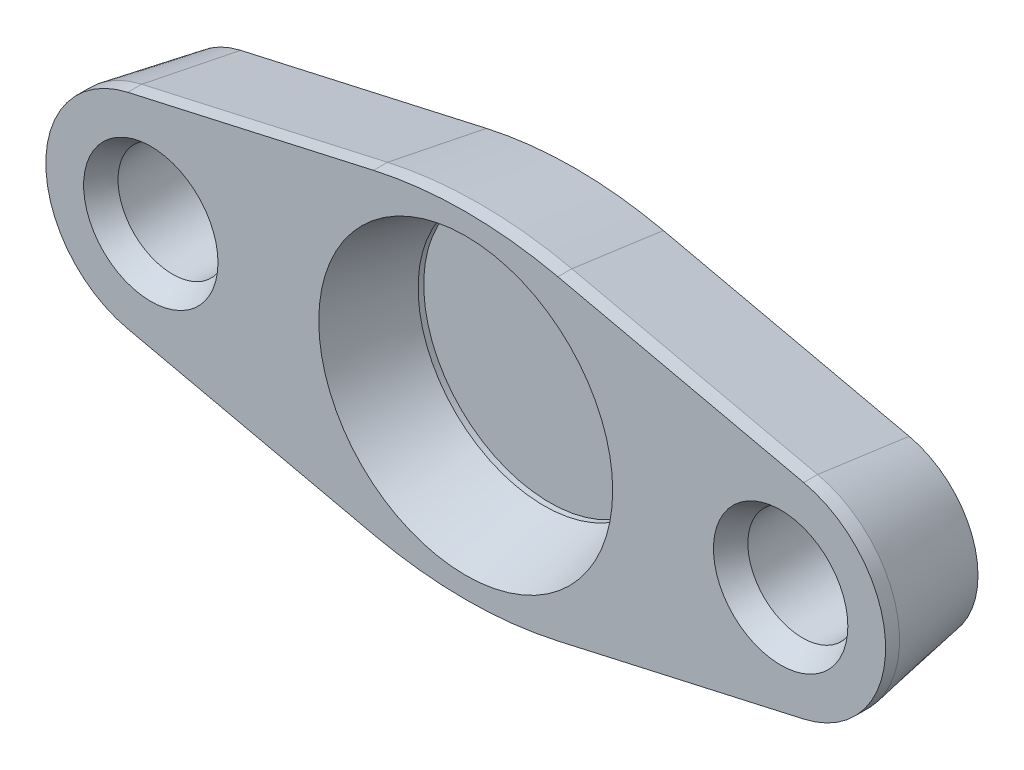
SolidWorks part; units mm, degrees
ref_plane "Front Plane" through (0, 0, 0) normal (0, 0, 1) x (1, 0, 0)
ref_plane "Top Plane" through (0, 0, 0) normal (0, 1, 0) x (1, 0, 0)
ref_plane "Right Plane" through (0, 0, 0) normal (1, 0, 0) x (0, 0, -1)
sketch "Sketch1" plane through (0, 0, 0) normal (0, 0, 1) x (1, 0, 0)
  line L0 (-8.0488, 2.439) -> (-2.1951, 3.7561)
  line L1 (2.1951, 3.7561) -> (8.0488, 2.439)
  line L2 (-8.0488, -2.439) -> (-2.1951, -3.7561)
  line L3 (2.1951, -3.7561) -> (8.0488, -2.439)
  line L4 (0, 9.0509) -> (0, -9.0509) construction
  line L5 (-11.5511, 0) -> (12.1784, 0) construction
  circle A0 centre (0, 0) radius 3 construction
  circle A1 centre (7.5, 0) radius 1.3
  circle A2 centre (-7.5, 0) radius 1.3
  arc A3 (-8.0488, 2.439) -> (-8.0488, -2.439) centre (-7.5, 0) ccw
  arc A4 (8.0488, -2.439) -> (8.0488, 2.439) centre (7.5, 0) ccw
  arc A5 (-2.1951, -3.7561) -> (2.1951, -3.7561) centre (0, 6) ccw
  arc A6 (-2.1951, 3.7561) -> (2.1951, 3.7561) centre (0, -6) cw
  point P7 (-11.3842, -1.6886)
  point P17 (0, -4.25)
  point P22 (0, 4.25)
  dimension "D1" = 2.6
  dimension "D2" = 15
  dimension "D3" = 5
  dimension "D4" = 6
  dimension "D5" = 10
  dimension "D6" = 6
extrude "Boss-Extrude1" add sketch "Sketch1" along normal blind 2.6
sketch "Sketch2" plane through (0, 0, 2.6) normal (0, 0, 1) x (1, 0, 0)
  circle A0 centre (0, 0) radius 3
  dimension "D1" = 6
extrude "Cut-Extrude1" cut sketch "Sketch2" against normal blind 2
chamfer "Chamfer1" distance 0.4 angle 80 8 edges at (-5.122, 3.0976, 0) (-10, 0, 0) (0, 4, 0) (-5.122, -3.0976, 0) (5.122, 3.0976, 0) (0, -4, 0) (10, 0, 0) (5.122, -3.0976, 0)
chamfer "Chamfer2" distance 0.5 angle 75 1 edges at (3, 0, 2.6)
chamfer "Chamfer3" distance 0.3 angle 60 2 edges at (8.8, 0, 2.6) (-6.2, 0, 2.6)
